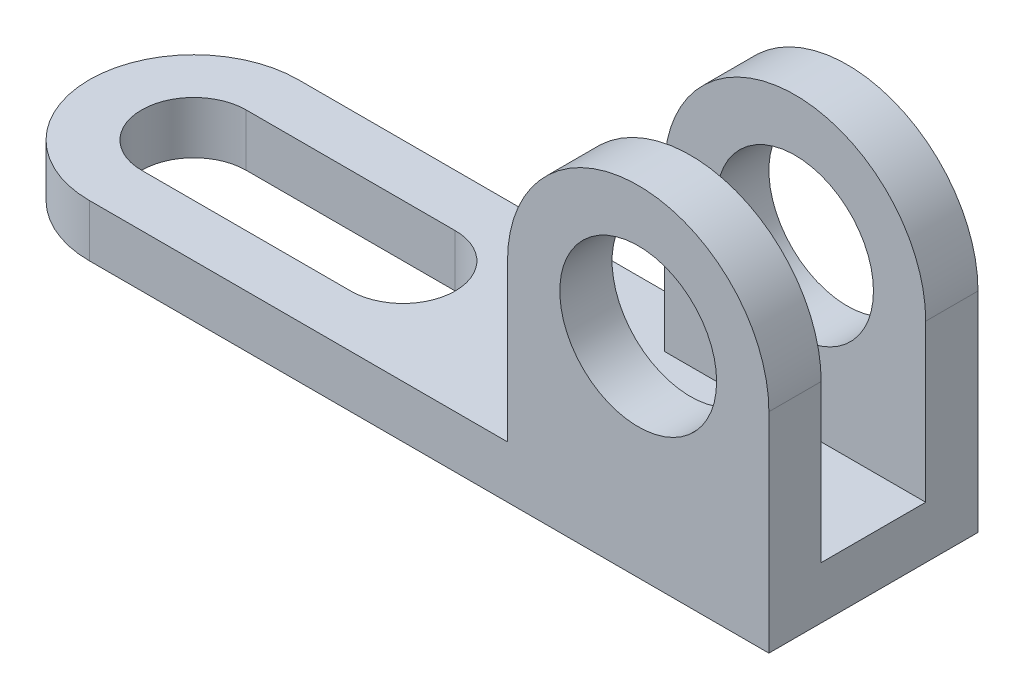
SolidWorks part; units mm, degrees
ref_plane "Front Plane" through (0, 0, 0) normal (0, 0, 1) x (1, 0, 0)
ref_plane "Top Plane" through (0, 0, 0) normal (0, 1, 0) x (1, 0, 0)
ref_plane "Right Plane" through (0, 0, 0) normal (1, 0, 0) x (0, 0, -1)
sketch "Sketch1" plane through (0, 0, 0) normal (0, 1, 0) x (1, 0, 0)
  line L0 (-65, 0) -> (-25, 0) construction
  line L1 (65, -20) -> (-65, -20)
  line L2 (65, -20) -> (65, 20)
  line L3 (65, 20) -> (-65, 20)
  line L5 (65, -20) -> (-53.7568, 16.5405) construction
  line L6 (65, 20) -> (-32.5, -10) construction
  line L7 (-65, 10) -> (-25, 10)
  line L8 (-65, -10) -> (-25, -10)
  arc A0 (-65, 10) -> (-65, -10) centre (-65, 0) ccw
  arc A1 (-25, -10) -> (-25, 10) centre (-25, 0) ccw
  arc A2 (-65, 20) -> (-65, -20) centre (-65, 0) ccw
  point P0 (0, 0)
  point P8 (-45, 0)
  dimension "D3" = 10
  dimension "D4" = 40
  dimension "D1" = 130
  dimension "D2" = 40
  dimension "40" = 40
extrude "Boss-Extrude1" add sketch "Sketch1" along normal mid plane 10
sketch "Sketch2" plane through (0, 0, 20) normal (0, 0, 1) x (1, 0, 0)
  line L1 (65, 5) -> (15, 5)
  line L2 (65, 5) -> (65, 35)
  line L4 (15, 5) -> (15, 35)
  arc A0 (65, 35) -> (15, 35) centre (40, 35) ccw
  circle A1 centre (40, 35) radius 15
  dimension "D3" = 50
  dimension "D4" = 30
  dimension "D1" = 30
  dimension "D2" = 50
extrude "Boss-Extrude2" add sketch "Sketch2" against normal blind 10
mirror "Mirror1" about plane through (0, 0, 0) normal (0, 0, 1) of "Boss-Extrude1", "Boss-Extrude2"
